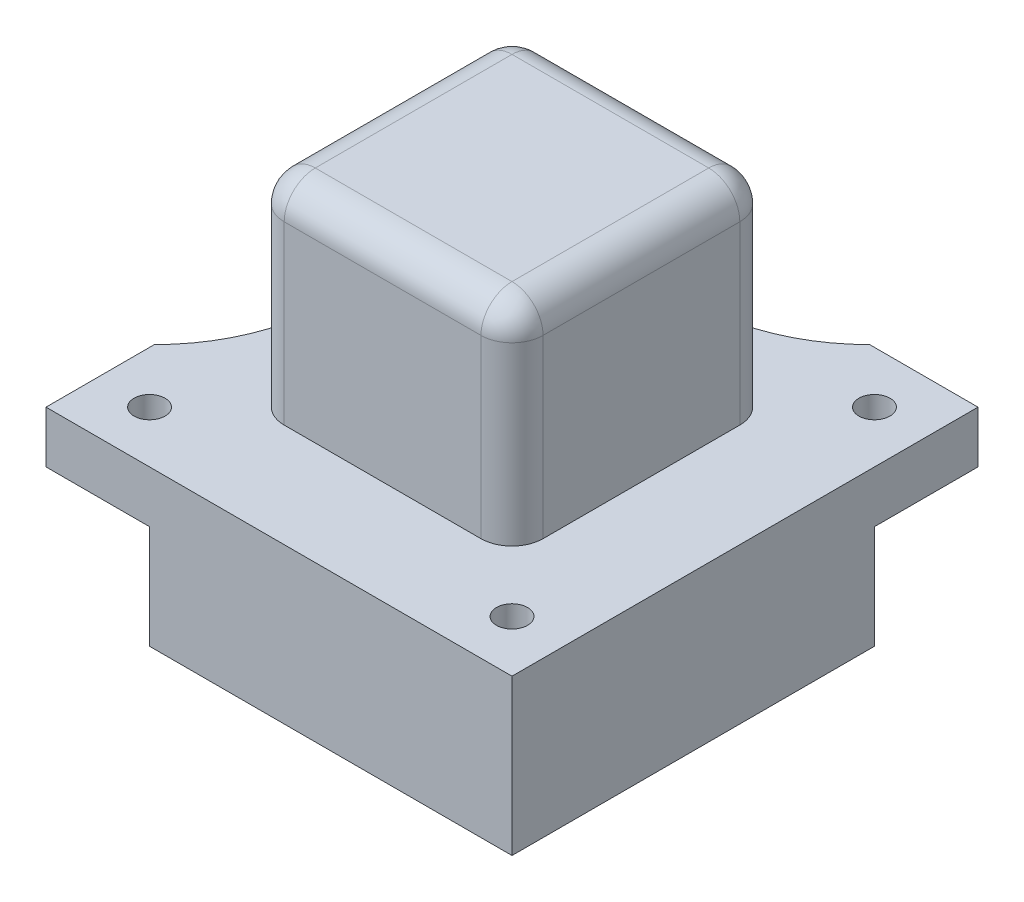
SolidWorks part; units mm, degrees
material "PET"
ref_plane "Front Plane" through (0, 0, 0) normal (0, 0, 1) x (1, 0, 0)
ref_plane "Top Plane" through (0, 0, 0) normal (0, 1, 0) x (1, 0, 0)
ref_plane "Right Plane" through (0, 0, 0) normal (1, 0, 0) x (0, 0, -1)
sketch "Sketch1" plane through (0, 0, 0) normal (0, 1, 0) x (1, 0, 0)
  line L1 (-21.8003, 27.3654) -> (23.1997, 27.3654)
  line L2 (-21.8003, 27.3654) -> (-21.8003, -17.6346)
  line L3 (-21.8003, -17.6346) -> (23.1997, -17.6346)
  line L4 (23.1997, 27.3654) -> (23.1997, -17.6346)
  dimension "D1" = 45
  dimension "D2" = 45
extrude "Boss-Extrude1" add sketch "Sketch1" along normal blind 15
sketch "Sketch2" plane through (0, 0, 0) normal (0, -1, 0) x (1, 0, 0)
  line L0 (-21.8003, 17.6346) -> (-11.8003, 17.6346)
  line L1 (-21.8003, 17.6346) -> (23.1997, 17.6346) construction
  line L2 (-11.8003, 17.6346) -> (-11.8003, -17.3654)
  line L3 (-11.8003, -17.3654) -> (23.1997, -17.3654)
  line L4 (23.1997, 17.6346) -> (23.1997, -27.3654) construction
  line L5 (23.1997, -17.3654) -> (23.1997, -27.3654)
  line L6 (23.1997, -27.3654) -> (-21.8003, -27.3654)
  line L7 (-21.8003, -27.3654) -> (-21.8003, 17.6346)
  dimension "D1" = 10
  dimension "D2" = 10
extrude "Cut-Extrude1" cut sketch "Sketch2" against normal blind 10
sketch "Sketch3" plane through (0, 10, 0) normal (0, -1, 0) x (1, 0, 0)
  line L0 (-11.3403, -27.3654) -> (12.7397, -27.3654)
  line L1 (-21.8003, 17.6346) -> (-21.8003, -27.3654) construction
  line L2 (-21.8003, 7.1746) -> (-21.8003, -16.9054)
  line L4 (-21.8003, -27.3654) -> (23.1997, -27.3654) construction
  arc A0 (-21.8003, 7.1746) -> (-21.8003, -16.9054) centre (-33.8019, -4.8654) cw
  arc A1 (-11.3403, -27.3654) -> (12.7397, -27.3654) centre (0.6997, -39.367) cw
  dimension "D5" = 17
  dimension "D6" = 17
extrude "Cut-Extrude2" cut sketch "Sketch3" against normal through all both and the other way through all
sketch "Sketch4" plane through (0, 10, 0) normal (0, -1, 0) x (1, 0, 0)
  line L0 (-21.8003, -17.4654) -> (-21.8003, -27.3654)
  line L1 (-21.8003, -16.9054) -> (-21.8003, -27.3654) construction
  line L2 (-21.8003, -27.3654) -> (-11.9003, -27.3654)
  line L3 (-21.8003, -27.3654) -> (-11.3403, -27.3654) construction
  arc A0 (-11.9003, -27.3654) -> (-21.8003, -17.4654) centre (-17.1102, -22.6753) ccw
  dimension "D3" = 7.01
extrude "Cut-Extrude3" cut sketch "Sketch4" against normal blind 2.5
sketch "Sketch5" plane through (0, 15, 0) normal (0, 1, 0) x (1, 0, 0)
  line L0 (23.1997, -17.6346) -> (23.1997, 27.3654) construction
  line L1 (-11.8003, 17.3654) -> (13.1997, 17.3654)
  line L2 (-11.8003, 17.3654) -> (-11.8003, -7.6346)
  line L3 (-11.8003, -7.6346) -> (13.1997, -7.6346)
  line L4 (13.1997, 17.3654) -> (13.1997, -7.6346)
  line L5 (-21.8003, -17.6346) -> (23.1997, -17.6346) construction
  dimension "D1" = 10
  dimension "D2" = 10
  dimension "D3" = 25
  dimension "D4" = 25
extrude "Boss-Extrude2" add sketch "Sketch5" along normal blind 20
fillet "Fillet1" radius 3 8 edges at (13.1997, 25, 7.6346) (13.1997, 35, -4.8654) (13.1997, 25, -17.3654) (0.6997, 35, -17.3654) (-11.8003, 25, -17.3654) (-11.8003, 35, -4.8654) (0.6997, 35, 7.6346) (-11.8003, 25, 7.6346)
sketch "Sketch6" plane through (0, 0, 0) normal (0, -1, 0) x (-1, 0, 0)
  line L0 (11.8003, -17.6346) -> (-23.1997, -17.6346) construction
  line L1 (-23.1997, -17.6346) -> (-23.1997, 17.3654) construction
  circle A0 centre (-0.6997, 4.8654) radius 6
  dimension "D1" = 22.5
  dimension "D2" = 22.5
  dimension "D3" = 12
extrude "Cut-Extrude4" cut sketch "Sketch6" against normal blind 28.9992
sketch "Sketch7" plane through (0, 28.9992, 0) normal (0, -1, 0) x (1, 0, 0)
  line L1 (-5.8003, -11.3654) -> (7.1997, -11.3654)
  line L2 (-5.8003, -11.3654) -> (-5.8003, 1.6346)
  line L3 (-5.8003, 1.6346) -> (7.1997, 1.6346)
  line L4 (7.1997, -11.3654) -> (7.1997, 1.6346)
  circle A1 centre (0.6997, -4.8654) radius 6 construction
  point P6 (7.1997, -4.8654)
  point P7 (0.6997, -11.3654)
  dimension "D1" = 0
  dimension "D2" = 0
  dimension "D3" = 13
  dimension "D4" = 13
extrude "Cut-Extrude5" cut sketch "Sketch7" along normal blind 13
fillet "Fillet2" radius 3 8 edges at (-5.8003, 22.4992, 1.6346) (0.6997, 28.9992, 1.6346) (7.1997, 22.4992, 1.6346) (7.1997, 22.4992, -11.3654) (-5.8003, 22.4992, -11.3654) (-5.8003, 28.9992, -4.8654) (0.6997, 28.9992, -11.3654) (7.1997, 28.9992, -4.8654)
sketch "Sketch8" plane through (0, 15, 0) normal (0, 1, 0) x (1, 0, 0)
  line L0 (-11.3403, 27.3654) -> (-21.8003, 27.3654) construction
  line L1 (-21.8003, 27.3654) -> (-21.8003, 16.9054) construction
  line L2 (23.1997, 27.3654) -> (12.7397, 27.3654) construction
  line L3 (23.1997, -17.6346) -> (23.1997, 27.3654) construction
  line L4 (-21.8003, -17.6346) -> (23.1997, -17.6346) construction
  line L5 (-21.8003, -7.1746) -> (-21.8003, -17.6346) construction
  circle A0 centre (-16.8003, 22.3654) radius 1.5
  circle A1 centre (18.1997, 22.3654) radius 1.5
  circle A2 centre (18.1997, -12.6346) radius 1.5
  circle A3 centre (-16.8003, -12.6346) radius 1.5
  dimension "D1" = 5
  dimension "D2" = 5
  dimension "D3" = 5
  dimension "D4" = 5
  dimension "D5" = 5
  dimension "D6" = 5
  dimension "D7" = 5
  dimension "D8" = 5
  dimension "D9" = 3
  dimension "D10" = 3
  dimension "D11" = 3
  dimension "D12" = 3
extrude "Cut-Extrude6" cut sketch "Sketch8" against normal through all both and the other way through all
